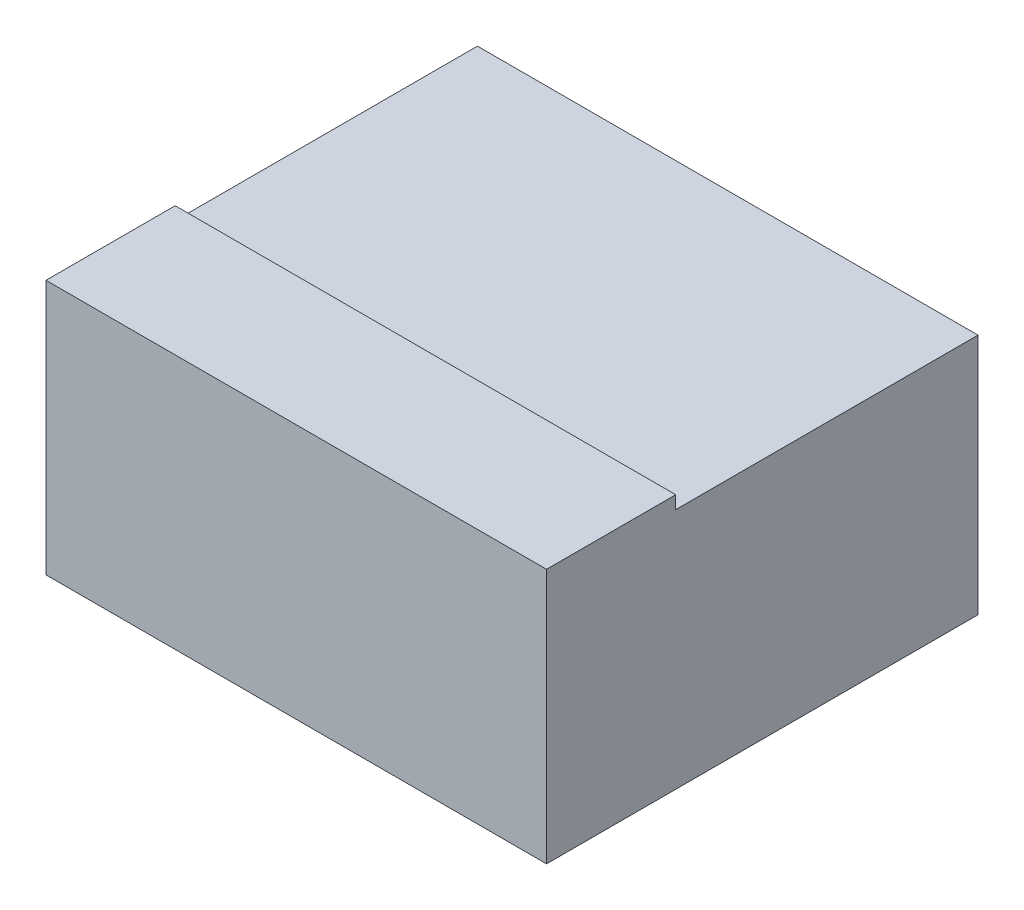
SolidWorks part; units mm, degrees
ref_plane "Front Plane" through (0, 0, 0) normal (0, 0, 1) x (1, 0, 0)
ref_plane "Top Plane" through (0, 0, 0) normal (0, 1, 0) x (1, 0, 0)
ref_plane "Right Plane" through (0, 0, 0) normal (1, 0, 0) x (0, 0, -1)
sketch "Sketch1" plane through (0, 0, 0) normal (0, 1, 0) x (1, 0, 0)
  line L1 (-38.75, 33.4) -> (38.75, 33.4)
  line L2 (-38.75, 33.4) -> (-38.75, -33.4)
  line L3 (-38.75, -33.4) -> (38.75, -33.4)
  line L4 (38.75, 33.4) -> (38.75, -33.4)
  line L5 (-38.75, 33.4) -> (38.75, -33.4) construction
  line L6 (-38.75, -33.4) -> (38.75, 33.4) construction
  point P0 (0, 0)
  dimension "D1" = 77.5
  dimension "D2" = 66.8
extrude "Boss-Extrude1" add sketch "Sketch1" along normal blind 37.5
sketch "Sketch3" plane through (0, 37.5, 0) normal (0, 1, 0) x (1, 0, 0)
  line L0 (-38.75, 33.4) -> (-38.75, -33.4) construction
  line L1 (38.75, -33.4) -> (-38.75, -33.4)
  line L2 (38.75, -33.4) -> (38.75, -13.4)
  line L3 (38.75, -13.4) -> (-38.75, -13.4)
  line L4 (-38.75, -33.4) -> (-38.75, -13.4)
  dimension "D1" = 20
extrude "Boss-Extrude2" add sketch "Sketch3" along normal blind 2
sketch "Sketch4" plane through (-38.75, 0, 0) normal (-1, 0, 0) x (0, 0, 1)
  line L1 (-33.4, 0) -> (-21.4, 0)
  line L2 (-33.4, 0) -> (-33.4, 12)
  line L3 (-33.4, 12) -> (-21.4, 12)
  line L4 (-21.4, 0) -> (-21.4, 12)
  dimension "D1" = 12
  dimension "D2" = 12
extrude "Boss-Extrude3" add sketch "Sketch4" along normal blind 5
